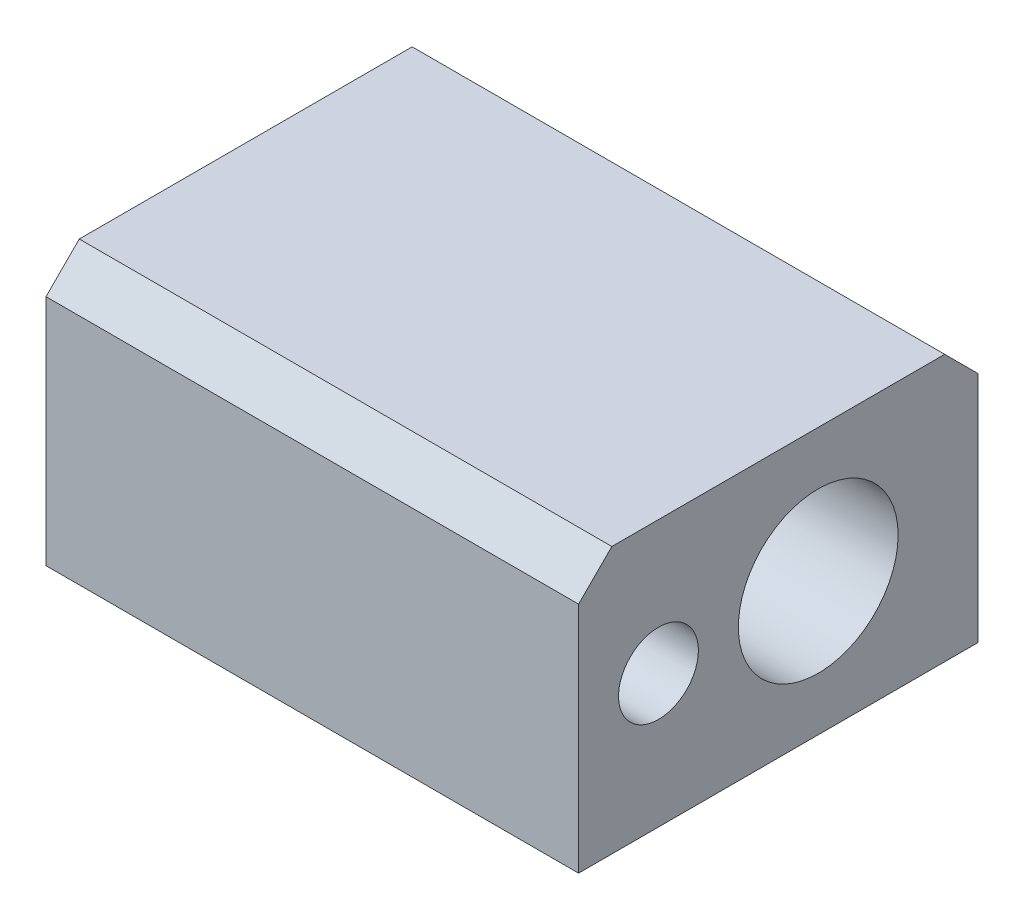
SolidWorks part; units mm, degrees
ref_plane "Front Plane" through (0, 0, 0) normal (1, 0, 0) x (0, 1, 0)
ref_plane "Top Plane" through (0, 0, 0) normal (0, 0, 1) x (0, 1, 0)
ref_plane "Right Plane" through (0, 0, 0) normal (0, 1, 0) x (-1, 0, 0)
sketch "Sketch1" plane through (0, 0, 0) normal (1, 0, 0) x (0, 1, 0)
  line L0 (0, -41.91) -> (0, 41.91) construction
  line L1 (25.4, -38.1) -> (-25.4, -38.1)
  line L2 (25.4, -38.1) -> (25.4, 38.1)
  line L3 (25.4, 38.1) -> (-25.4, 38.1)
  line L4 (-25.4, -38.1) -> (-25.4, 38.1)
  line L5 (25.4, -38.1) -> (-25.4, 38.1) construction
  line L6 (25.4, 38.1) -> (-25.4, -38.1) construction
  circle A0 centre (0, -7.62) radius 15.24
  circle A1 centre (0, 22.86) radius 7.62
  point P0 (0, 0)
  dimension "D3" = 30.48
  dimension "D5" = 15.24
  dimension "D1" = 50.8
  dimension "D2" = 76.2
  dimension "D4" = 30.48
  dimension "D6" = 15.24
extrude "Boss-Extrude1" add sketch "Sketch1" along normal blind 101.6
chamfer "Chamfer1" distance 6.35 angle 45 2 edges at (50.8, 25.4, -38.1) (50.8, 25.4, 38.1)
